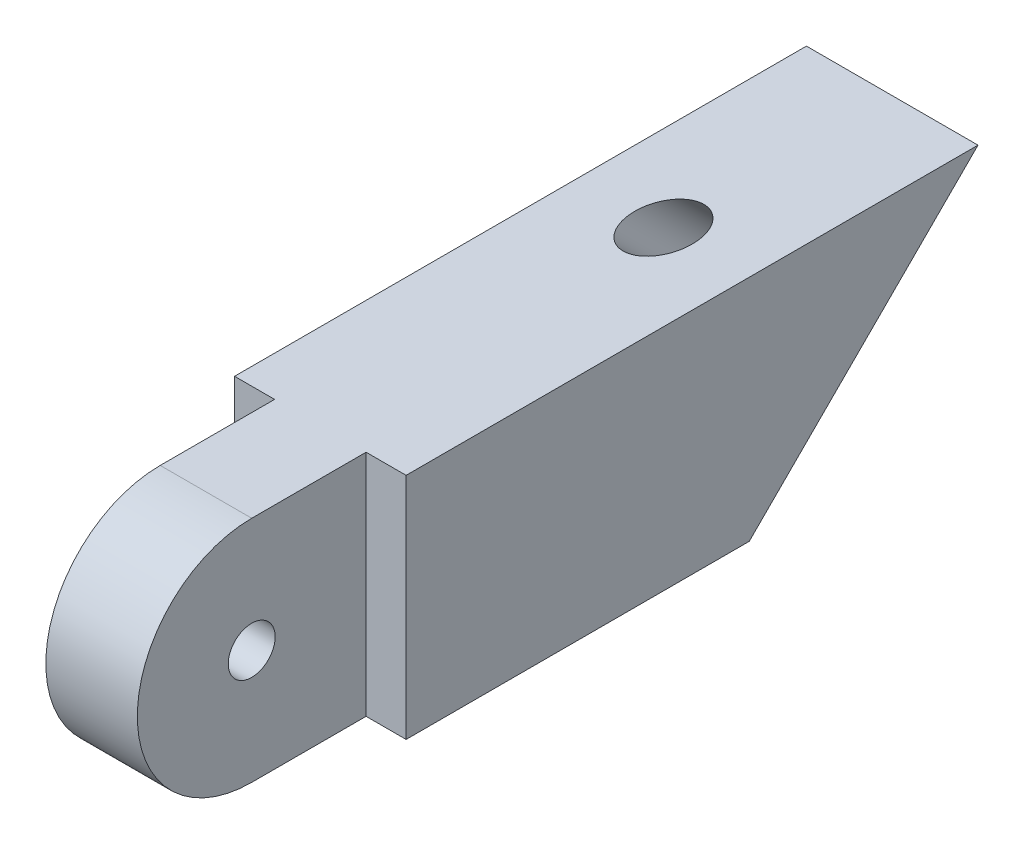
SolidWorks part; units mm, degrees
ref_plane "Front Plane" through (0, 0, 0) normal (0, 0, 1) x (1, 0, 0)
ref_plane "Top Plane" through (0, 0, 0) normal (0, 1, 0) x (1, 0, 0)
ref_plane "Right Plane" through (0, 0, 0) normal (1, 0, 0) x (0, 0, -1)
sketch "Sketch6" plane through (0, 0, 0) normal (1, 0, 0) x (0, 0, -1)
  line L0 (0, 0) -> (100, 0) construction
  line L1 (0, 0) -> (0, 57.8268) construction
  line L3 (-70, 20) -> (70, 20)
  line L4 (-70, 20) -> (-70, -20)
  line L5 (-70, -20) -> (70, -20)
  line L6 (70, 20) -> (70, -20)
  line L7 (-70, 20) -> (70, -20) construction
  line L8 (-70, -20) -> (70, 20) construction
extrude "Boss-Extrude2" add sketch "Sketch6" along normal blind 30
sketch "Sketch9" plane through (0, 0, 70) normal (0, 0, 1) x (1, 0, 0)
  line L0 (0, 20) -> (7, 20)
  line L1 (30, 20) -> (0, 20) construction
  line L2 (7, 20) -> (7, -20)
  line L3 (30, -20) -> (0, -20) construction
  line L4 (7, -20) -> (0, -20)
  line L5 (0, -20) -> (0, 20)
  line L6 (30, 20) -> (23, 20)
  line L7 (23, 20) -> (23, -20)
  line L8 (23, -20) -> (30, -20)
  line L9 (30, -20) -> (30, 20)
extrude "Cut-Extrude3" cut sketch "Sketch9" against normal blind 40
sketch "Sketch18" plane through (23, 0, 0) normal (1, 0, 0) x (0, 0, -1)
  line L0 (-70, 20) -> (-70, 0)
  line L1 (-70, 20) -> (-70, -20) construction
  line L2 (-30, 20) -> (-70, 20) construction
  line L3 (-50, 20) -> (-70, 20)
  arc A0 (-70, 0) -> (-50, 20) centre (-50, 0) cw
extrude "Cut-Extrude6" cut sketch "Sketch18" against normal blind 45
sketch "Sketch19" plane through (23, 0, 0) normal (1, 0, 0) x (0, 0, -1)
  line L0 (-70, 0) -> (-70, -20)
  line L1 (-70, -20) -> (-50, -20)
  line L2 (-30, -20) -> (-70, -20) construction
  arc A0 (-50, -20) -> (-70, 0) centre (-50, 0) cw
extrude "Cut-Extrude7" cut sketch "Sketch19" against normal blind 45
sketch "Sketch22" plane through (23, 0, 0) normal (1, 0, 0) x (0, 0, -1)
  circle A0 centre (-50, 0) radius 4.1
  dimension "D1" = 8.2
extrude "Cut-Extrude8" cut sketch "Sketch22" against normal blind 45 contours A0
sketch "Sketch24" plane through (30, 0, 0) normal (1, 0, 0) x (0, 0, -1)
  line L0 (70, 20) -> (30, -20)
  line L1 (-30, -20) -> (70, -20) construction
  line L2 (30, -20) -> (70, -20)
  line L3 (70, -20) -> (70, 20)
extrude "Cut-Extrude9" cut sketch "Sketch24" against normal blind 45
sketch "Sketch26" plane through (0, -25, -25) normal (0, -0.7071, -0.7071) x (1, 0, 0)
  line L0 (0, -7.0711) -> (30, -63.6396) construction
  line L1 (30, -7.0711) -> (0, -63.6396) construction
  circle A1 centre (15, -35.3553) radius 10
extrude "Cut-Extrude10" cut sketch "Sketch26" against normal blind 10 contours A1
sketch "Sketch28" plane through (0, -17.9289, -17.9289) normal (0, -0.7071, -0.7071) x (1, 0, 0)
  circle A0 centre (15, -35.3553) radius 5
extrude "Cut-Extrude11" cut sketch "Sketch28" against normal blind 35 contours A0
